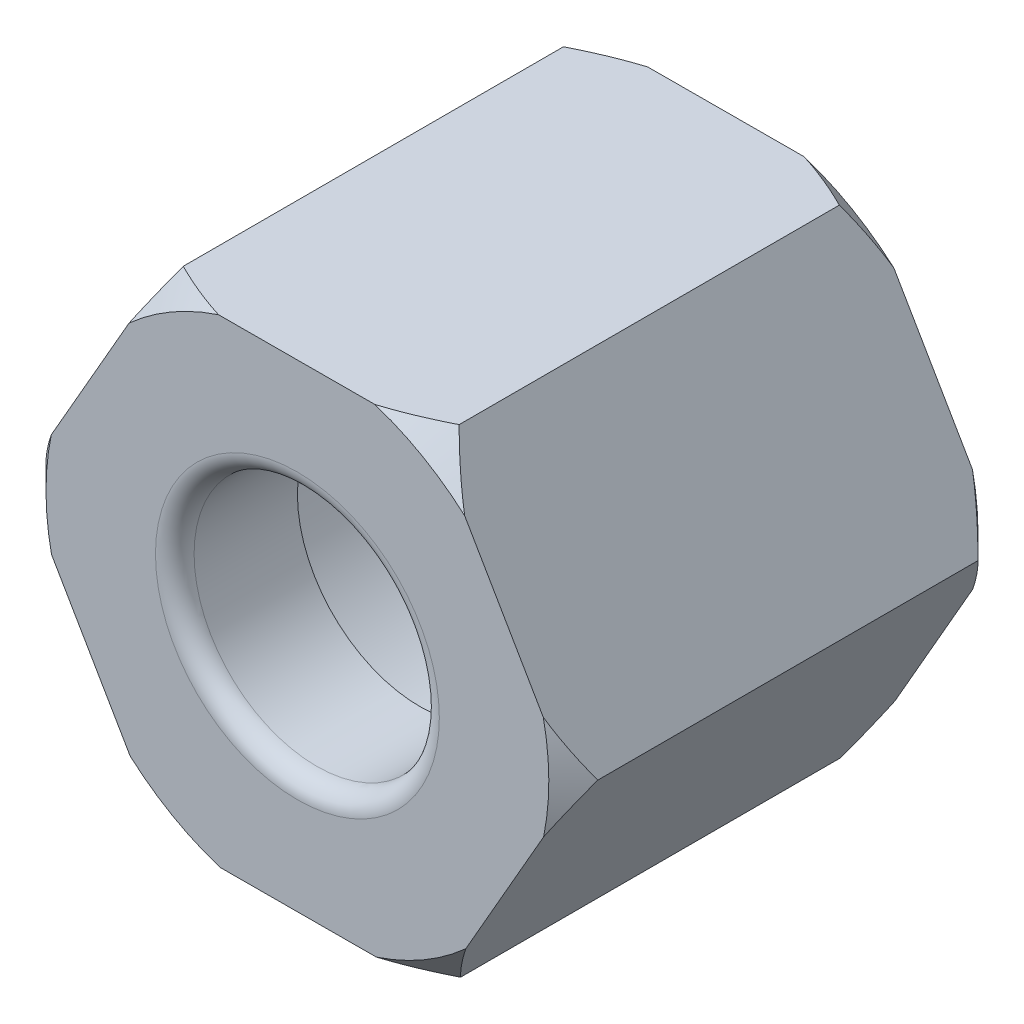
SolidWorks part; units mm, degrees
material "Latão"
ref_plane "Plano frontal" through (0, 0, 0) normal (0, 0, 1) x (1, 0, 0)
ref_plane "Plano superior" through (0, 0, 0) normal (0, 1, 0) x (1, 0, 0)
ref_plane "Plano direito" through (0, 0, 0) normal (1, 0, 0) x (0, 0, -1)
sketch "Esboço1" plane through (0, 0, 0) normal (0, 0, 1) x (1, 0, 0)
  line L1 (3.5535, 6.1973) -> (-3.5903, 6.176)
  line L2 (-3.5903, 6.176) -> (-7.1437, -0.0213)
  line L3 (-7.1437, -0.0213) -> (-3.5535, -6.1973)
  line L4 (-3.5535, -6.1973) -> (3.5903, -6.176)
  line L5 (3.5903, -6.176) -> (7.1437, 0.0213)
  line L6 (7.1437, 0.0213) -> (3.5535, 6.1973)
  circle A0 centre (0, 0) radius 7.1438 construction
  circle A1 centre (0, 0) radius 3.175
  dimension "D1" = 14.2875
  dimension "D2" = 6.35
extrude "Ressalto-extrusão1" add sketch "Esboço1" along normal blind 11.1125
sketch "Esboço2" plane through (0, 0, 0) normal (0, 0, -1) x (-1, 0, 0)
  circle A0 centre (0, 0) radius 4.9609
  dimension "D1" = 9.9219
extrude "Corte-extrusão1" cut sketch "Esboço2" against normal blind 7.9375
cosmetic thread "Representação de rosca1" parameters "D1"=7, "D2"=11.1125
fillet "Filete1" radius 0.5 1 edges at (3.175, 0, 11.1125)
ref_axis "Eixo1" through (0, 0, 23.3956) along (0, 0, -1)
sketch "Esboço4" plane through (0, 0, 0) normal (0, 1, 0) x (1, 0, 0)
  line L0 (6.4097, -16.2661) -> (6.4097, -11.2125)
  line L1 (6.4097, -16.2661) -> (9.2696, -16.2661)
  line L2 (9.2696, -16.2661) -> (9.2696, -8.3526)
  line L3 (6.4097, -11.2125) -> (9.2696, -8.3526)
  line L4 (7.1437, -11.1125) -> (3.5535, -11.1125) construction
  line L5 (7.1437, -5.5562) -> (16.2697, -5.5562) construction
  line L6 (7.1437, -11.1125) -> (7.1437, 0) construction
  line L7 (6.4097, 5.1536) -> (9.2696, 5.1536)
  line L8 (9.2696, 5.1536) -> (9.2696, -2.7599)
  line L9 (6.4097, 0.1) -> (9.2696, -2.7599)
  line L10 (6.4097, 5.1536) -> (6.4097, 0.1)
  dimension "D1" = 45
  dimension "D2" = 0.1
revolve "Corte-Revolução4" cut sketch "Esboço4" angle 360 about axis through (0, 0, 23.3956) along (0, 0, -1)
